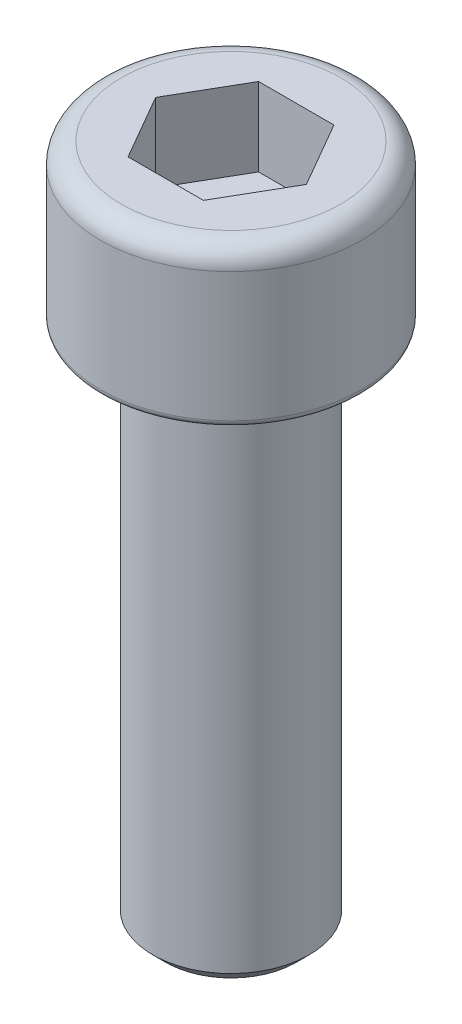
SolidWorks part; units mm, degrees
material "Plain Carbon Steel"
ref_plane "Front Plane" through (0, 0, 0) normal (0, 0, 1) x (1, 0, 0)
ref_plane "Top Plane" through (0, 0, 0) normal (0, 1, 0) x (1, 0, 0)
ref_plane "Right Plane" through (0, 0, 0) normal (1, 0, 0) x (0, 0, -1)
sketch "Sketch1" plane through (0, 0, 0) normal (0, 0, 1) x (1, 0, 0)
  line L0 (0, 0) -> (5, 0)
  line L1 (5, 0) -> (5, -6)
  line L2 (5, -6) -> (3, -6)
  line L3 (3, -6) -> (3, -26)
  line L4 (3, -26) -> (0, -26)
  line L5 (0, -26) -> (0, 0)
  line L6 (0, -31) -> (0, 5) construction
  dimension "D1" = 5
  dimension "D2" = 5
  dimension "H" = 6
  dimension "L" = 20
  dimension "D" = 6
  dimension "A" = 10
revolve "Revolve1" add sketch "Sketch1" angle 360 about L6
sketch "Sketch2" plane through (0, 0, 0) normal (0, 1, 0) x (1, 0, 0)
  line L7 (2.8868, 0) -> (1.4434, 2.5)
  line L8 (1.4434, 2.5) -> (-1.4434, 2.5)
  line L9 (-1.4434, 2.5) -> (-2.8868, 0)
  line L10 (-2.8868, 0) -> (-1.4434, -2.5)
  line L11 (-1.4434, -2.5) -> (1.4434, -2.5)
  line L12 (1.4434, -2.5) -> (2.8868, 0)
  circle A0 centre (0, 0) radius 2.5 construction
  dimension "D1" = 5
extrude "Cut-Extrude1" cut sketch "Sketch2" against normal blind 3
fillet "Fillet3" radius 0.8 1 edges at (0, 0, -5)
chamfer "Chamfer1" distance 0.5 angle 45 1 edges at (0, -26, -3)
cosmetic thread "Cosmetic Thread1" parameters "B"=7, "D2"=4.891
fillet "Fillet4" radius 0.25 2 edges at (0, -6, -3) (0, -6, -5)
